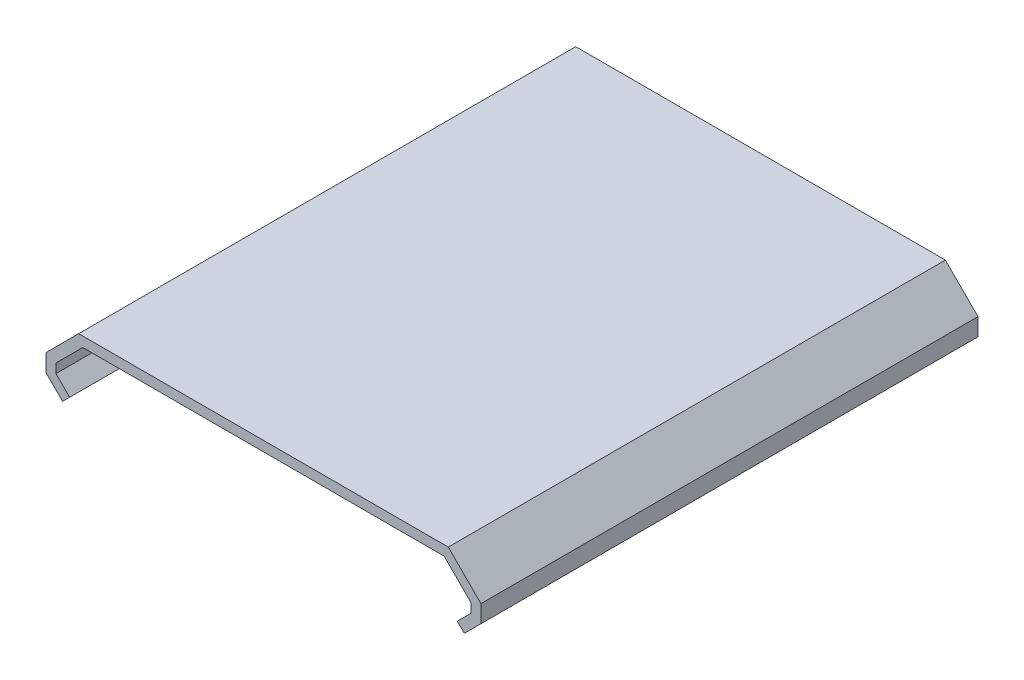
SolidWorks part; units mm, degrees
ref_plane "前视基准面" through (0, 0, 0) normal (0, 0, 1) x (1, 0, 0)
ref_plane "上视基准面" through (0, 0, 0) normal (0, 1, 0) x (1, 0, 0)
ref_plane "右视基准面" through (0, 0, 0) normal (1, 0, 0) x (0, 0, -1)
other "Configuration Table"
sketch "草图1" plane through (0, 0, 0) normal (0, 0, 1) x (1, 0, 0)
  line L0 (0, 52) -> (-72.7071, 52)
  line L1 (-72.7071, 52) -> (-83.5, 41.2071)
  line L2 (-83.5, 41.2071) -> (-83.5, 37.5)
  line L3 (-83.5, 37.5) -> (-78, 32)
  line L4 (-83, 37) -> (-77, 31) construction
  line L6 (-77, 47) -> (-83, 41) construction
  line L7 (-83, 41) -> (-83, 37) construction
  line L8 (77, 47) -> (74, 47) construction
  line L9 (-77, 31) -> (-77, 0) construction
  line L10 (0, 0) -> (0, 52) construction
  line L11 (0, 52) -> (72.7071, 52)
  line L12 (83.5, 37.5) -> (78, 32)
  line L13 (83.5, 41.2071) -> (83.5, 37.5)
  line L14 (72.7071, 52) -> (83.5, 41.2071)
  dimension "D1" = 0.5
  dimension "D2" = 0.5
  dimension "D3" = 5
  dimension "D4" = 1
extrude "拉伸-薄壁1" add sketch "草图1" against normal blind 200 thin
sketch "草图2" plane through (0, 0, -200) normal (0, 0, -1) x (-1, 0, 0)
  line L0 (-8.4142, 52) -> (3, 52)
  line L1 (72.7071, 52) -> (-72.7071, 52) construction
  line L2 (3, 52) -> (3, 40.5858)
  line L3 (3, 40.5858) -> (-8.4142, 52)
  line L5 (3, 39.1716) -> (3, 3) construction
  line L6 (-4.794, 46.9656) -> (3, 39.1716) construction
  dimension "D1" = 1
extrude "凸台-拉伸1" add sketch "草图2" against normal blind 18
